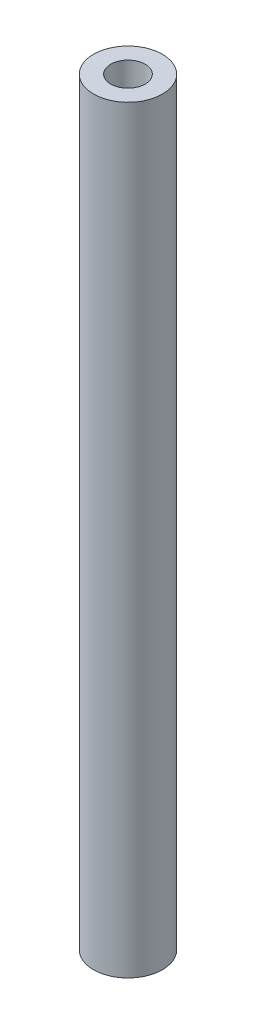
SolidWorks part; units mm, degrees
ref_plane "Front Plane" through (0, 0, 0) normal (0, 0, 1) x (1, 0, 0)
ref_plane "Top Plane" through (0, 0, 0) normal (0, 1, 0) x (1, 0, 0)
ref_plane "Right Plane" through (0, 0, 0) normal (1, 0, 0) x (0, 0, -1)
sketch "Sketch1" plane through (0, 0, 0) normal (0, 1, 0) x (1, 0, 0)
  circle A0 centre (-58.1882, -19.3502) radius 2.5
extrude "Boss-Extrude2" add sketch "Sketch1" along normal blind 55 contours A0
sketch "Sketch5" plane through (0, 55, 0) normal (0, 1, 0) x (1, 0, 0)
  circle A0 centre (-58.1882, -19.3502) radius 1.1509
hole_wizard "Ø2.5 (2.5) Diameter Hole1" positions "Sketch6" profile "Sketch7" hole size "Ø2.5" standard "ANSI Metric" end condition through all
sketch "Sketch6" plane through (0, 55, 0) normal (0, 1, 0) x (1, 0, 0)
  point P0 (-58.1882, -19.3502)
sketch "Sketch7" plane through (-58.1882, 55, 19.3502) normal (1, 0, 0) x (0, 0, 1)
  line L0 (0, 0) -> (0, 55)
  line L1 (0, 55) -> (1.25, 55)
  line L2 (1.25, 55) -> (1.25, 0)
  line L5 (1.25, 0) -> (0, 0)
  line L11 (0, -6.35) -> (0, 107.95) construction
  dimension "Thru Hole Dia." = 2.5
  dimension "Thru Hole Depth" = 55
